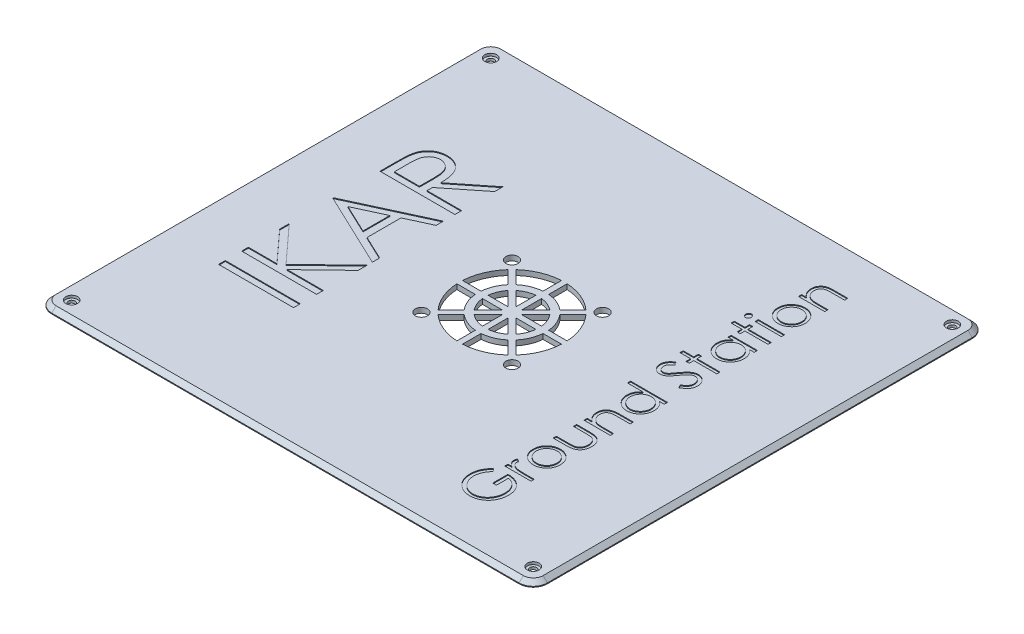
SolidWorks part; units mm, degrees
ref_plane "Płaszczyzna przednia" through (0, 0, 0) normal (0, 0, 1) x (1, 0, 0)
ref_plane "Płaszczyzna górna" through (0, 0, 0) normal (0, 1, 0) x (1, 0, 0)
ref_plane "Płaszczyzna prawa" through (0, 0, 0) normal (1, 0, 0) x (0, 0, -1)
sketch "Szkic1" plane through (0, 0, 0) normal (0, 1, 0) x (1, 0, 0)
  line L1 (87.5, -80) -> (-87.5, -80)
  line L2 (87.5, -80) -> (87.5, 80)
  line L3 (87.5, 80) -> (-87.5, 80)
  line L4 (-87.5, -80) -> (-87.5, 80)
  line L5 (87.5, -80) -> (-87.5, 80) construction
  line L6 (87.5, 80) -> (-87.5, -80) construction
  point P0 (0, 0)
  dimension "D1" = 175
  dimension "D2" = 160
extrude "Dodanie-wyciągnięcie1" add sketch "Szkic1" along normal blind 1.8
fillet "Zaokrąglenie1" radius 5 4 edges at (-87.5, 0.9, -80) (87.5, 0.9, -80) (87.5, 0.9, 80) (-87.5, 0.9, 80)
sketch "Szkic2" plane through (0, 1.8, 0) normal (0, 1, 0) x (1, 0, 0)
  line L0 (82.5, 80) -> (-82.5, 80) construction
  line L1 (-87.5, 75) -> (-87.5, -75) construction
  line L2 (87.5, -75) -> (87.5, 75) construction
  line L3 (-87.5, 0) -> (87.5, 0) construction
  circle A0 centre (-81.5, 74) radius 1.2
  circle A1 centre (81.5, 74) radius 1.2
  circle A2 centre (81.5, -74) radius 1.2
  circle A3 centre (-81.5, -74) radius 1.2
  dimension "D3" = 2.4
  dimension "D4" = 6
  dimension "D6" = 2.4
  dimension "D1" = 6
  dimension "D2" = 6
  dimension "D5" = 6
extrude "Wytnij-wyciągnięcie1" cut sketch "Szkic2" against normal through all
sketch "Szkic3" plane through (0, 1.8, 0) normal (0, 1, 0) x (1, 0, 0)
  line L0 (-16, 0) -> (16, 0) construction
  line L1 (16, 16) -> (16, -16) construction
  line L2 (0, 0) -> (0, 10.869) construction
  line L3 (-1, 0) -> (1, 0) construction
  line L4 (-1, -2.4142) -> (-1, -9.4472)
  line L5 (1, -2.4142) -> (1, -9.4472)
  line L6 (-1, 0) -> (-1, -2.2913) construction
  line L7 (1, 0) -> (1, -2.2913) construction
  line L8 (1, -9.4472) -> (1, -11.9583) construction
  line L9 (1, -11.9583) -> (1, -18.473)
  line L10 (-1, -9.4472) -> (-1, -11.9583) construction
  line L11 (-1, -11.9583) -> (-1, -18.473)
  line L12 (-1, -2.4142) -> (-5.9731, -7.3873)
  line L13 (-2.4142, -1) -> (-7.3873, -5.9731)
  line L14 (-7.7487, -9.1629) -> (-12.3552, -13.7695)
  line L39 (-9.1629, -7.7487) -> (-13.7695, -12.3552)
  line L40 (-2.4142, -1) -> (-9.4472, -1)
  line L41 (-2.4142, 1) -> (-9.4472, 1)
  line L42 (-11.9583, -1) -> (-18.473, -1)
  line L43 (-11.9583, 1) -> (-18.473, 1)
  line L44 (-2.4142, 1) -> (-7.3873, 5.9731)
  line L45 (-1, 2.4142) -> (-5.9731, 7.3873)
  line L46 (-9.1629, 7.7487) -> (-13.7695, 12.3552)
  line L47 (-7.7487, 9.1629) -> (-12.3552, 13.7695)
  line L48 (-1, 2.4142) -> (-1, 9.4472)
  line L49 (1, 2.4142) -> (1, 9.4472)
  line L50 (-1, 11.9583) -> (-1, 18.473)
  line L51 (1, 11.9583) -> (1, 18.473)
  line L52 (1, 2.4142) -> (5.9731, 7.3873)
  line L53 (2.4142, 1) -> (7.3873, 5.9731)
  line L54 (7.7487, 9.1629) -> (12.3552, 13.7695)
  line L55 (9.1629, 7.7487) -> (13.7695, 12.3552)
  line L56 (2.4142, 1) -> (9.4472, 1)
  line L57 (2.4142, -1) -> (9.4472, -1)
  line L58 (11.9583, 1) -> (18.473, 1)
  line L59 (11.9583, -1) -> (18.473, -1)
  line L60 (2.4142, -1) -> (7.3873, -5.9731)
  line L61 (1, -2.4142) -> (5.9731, -7.3873)
  line L62 (9.1629, -7.7487) -> (13.7695, -12.3552)
  line L63 (7.7487, -9.1629) -> (12.3552, -13.7695)
  line L64 (-2.3273, 0.9131) -> (-2.4142, 1) construction
  line L65 (-2.2913, 1) -> (-2.4142, 1) construction
  line L66 (-1, 2.2913) -> (-1, 2.4142) construction
  line L67 (-0.9131, 2.3273) -> (-1, 2.4142) construction
  line L68 (1, 2.2913) -> (1, 2.4142) construction
  line L69 (0.9131, 2.3273) -> (1, 2.4142) construction
  line L70 (2.2913, 1) -> (2.4142, 1) construction
  line L71 (2.3273, 0.9131) -> (2.4142, 1) construction
  line L72 (2.2913, -1) -> (2.4142, -1) construction
  line L73 (2.3273, -0.9131) -> (2.4142, -1) construction
  line L74 (1, -2.2913) -> (1, -2.4142) construction
  line L75 (0.9131, -2.3273) -> (1, -2.4142) construction
  line L76 (-0.9131, -2.3273) -> (-1, -2.4142) construction
  line L77 (-1, -2.2913) -> (-1, -2.4142) construction
  line L78 (-2.3273, -0.9131) -> (-2.4142, -1) construction
  line L79 (-2.2913, -1) -> (-2.4142, -1) construction
  circle A0 centre (16, 16) radius 2.15
  circle A1 centre (16, -16) radius 2.15
  circle A2 centre (-16, -16) radius 2.15
  circle A3 centre (-16, 16) radius 2.15
  circle A13 centre (0, 0) radius 18.5
  arc A17 (2.2913, -1) -> (2.3273, -0.9131) centre (0, 0) ccw construction
  arc A19 (-5.9731, -7.3873) -> (-1, -9.4472) centre (0, 0) ccw
  arc A23 (-7.7487, -9.1629) -> (-1, -11.9583) centre (0, 0) ccw
  arc A27 (-9.1629, -7.7487) -> (-7.7487, -9.1629) centre (0, 0) ccw construction
  arc A30 (-7.3873, -5.9731) -> (-5.9731, -7.3873) centre (0, 0) ccw construction
  arc A31 (7.7487, -9.1629) -> (9.1629, -7.7487) centre (0, 0) ccw construction
  arc A32 (9.1629, -7.7487) -> (11.9583, -1) centre (0, 0) ccw
  arc A34 (5.9731, -7.3873) -> (7.3873, -5.9731) centre (0, 0) ccw construction
  arc A36 (7.3873, -5.9731) -> (9.4472, -1) centre (0, 0) ccw
  arc A38 (1, -2.2913) -> (2.2913, -1) centre (0, 0) ccw construction
  arc A39 (-2.2913, -1) -> (-1, -2.2913) centre (0, 0) ccw construction
  arc A41 (-1, -2.2913) -> (-0.9131, -2.3273) centre (0, 0) ccw construction
  arc A43 (-1, 2.2913) -> (-2.2913, 1) centre (0, 0) ccw construction
  arc A44 (-2.2913, 1) -> (-2.3273, 0.9131) centre (0, 0) ccw construction
  arc A45 (2.2913, 1) -> (1, 2.2913) centre (0, 0) ccw construction
  arc A46 (1, 2.2913) -> (0.9131, 2.3273) centre (0, 0) ccw construction
  arc A47 (9.1629, 7.7487) -> (7.7487, 9.1629) centre (0, 0) ccw construction
  arc A48 (7.7487, 9.1629) -> (1, 11.9583) centre (0, 0) ccw
  arc A49 (7.3873, 5.9731) -> (5.9731, 7.3873) centre (0, 0) ccw construction
  arc A50 (5.9731, 7.3873) -> (1, 9.4472) centre (0, 0) ccw
  arc A51 (1, 11.9583) -> (-1, 11.9583) centre (0, 0) ccw construction
  arc A52 (-1, 11.9583) -> (-7.7487, 9.1629) centre (0, 0) ccw
  arc A53 (0, 9.5) -> (-1, 9.4472) centre (0, 0) ccw construction
  arc A54 (-1, 9.4472) -> (-5.9731, 7.3873) centre (0, 0) ccw
  arc A55 (1, 9.4472) -> (0, 9.5) centre (0, 0) ccw construction
  arc A56 (-7.7487, 9.1629) -> (-9.1629, 7.7487) centre (0, 0) ccw construction
  arc A57 (-9.1629, 7.7487) -> (-11.9583, 1) centre (0, 0) ccw
  arc A58 (-5.9731, 7.3873) -> (-7.3873, 5.9731) centre (0, 0) ccw construction
  arc A59 (-7.3873, 5.9731) -> (-9.4472, 1) centre (0, 0) ccw
  arc A60 (-11.9583, 1) -> (-12, 0) centre (0, 0) ccw construction
  arc A61 (-11.9583, -1) -> (-9.1629, -7.7487) centre (0, 0) ccw
  arc A62 (-9.5, 0) -> (-9.4472, -1) centre (0, 0) ccw construction
  arc A63 (-9.4472, -1) -> (-7.3873, -5.9731) centre (0, 0) ccw
  arc A64 (-9.4472, 1) -> (-9.5, 0) centre (0, 0) ccw construction
  arc A65 (-12, 0) -> (-11.9583, -1) centre (0, 0) ccw construction
  arc A66 (0.9131, 2.3273) -> (0, 2.5) centre (0, 0) ccw construction
  arc A67 (-0.9131, 2.3273) -> (-1, 2.2913) centre (0, 0) ccw construction
  arc A68 (0, 2.5) -> (-0.9131, 2.3273) centre (0, 0) ccw construction
  arc A69 (-2.5, 0) -> (-2.3273, -0.9131) centre (0, 0) ccw construction
  arc A70 (-2.3273, -0.9131) -> (-2.2913, -1) centre (0, 0) ccw construction
  arc A71 (-2.3273, 0.9131) -> (-2.5, 0) centre (0, 0) ccw construction
  arc A72 (2.3273, -0.9131) -> (2.5, 0) centre (0, 0) ccw construction
  arc A73 (2.3273, 0.9131) -> (2.2913, 1) centre (0, 0) ccw construction
  arc A74 (2.5, 0) -> (2.3273, 0.9131) centre (0, 0) ccw construction
  arc A75 (-0.9131, -2.3273) -> (0.9131, -2.3273) centre (0, 0) ccw construction
  arc A76 (0.9131, -2.3273) -> (1, -2.2913) centre (0, 0) ccw construction
  arc A77 (-1, -9.4472) -> (1, -9.4472) centre (0, 0) ccw construction
  arc A78 (1, -9.4472) -> (5.9731, -7.3873) centre (0, 0) ccw
  arc A79 (-1, -11.9583) -> (1, -11.9583) centre (0, 0) ccw construction
  arc A80 (1, -11.9583) -> (7.7487, -9.1629) centre (0, 0) ccw
  arc A81 (9.4472, -1) -> (9.5, 0) centre (0, 0) ccw construction
  arc A82 (9.4472, 1) -> (7.3873, 5.9731) centre (0, 0) ccw
  arc A83 (9.5, 0) -> (9.4472, 1) centre (0, 0) ccw construction
  arc A84 (12, 0) -> (11.9583, 1) centre (0, 0) ccw construction
  arc A85 (11.9583, 1) -> (9.1629, 7.7487) centre (0, 0) ccw
  arc A86 (11.9583, -1) -> (12, 0) centre (0, 0) ccw construction
  circle A87 centre (0, 0) radius 29.0182
  point P20 (0, 0)
  point P86 (0, 0)
  dimension "D3" = 4.3
  dimension "D4" = 4.3
  dimension "D5" = 5
  dimension "D6" = 6.5
  dimension "D9" = 8
  dimension "D1" = 37
  dimension "D7" = 2.5
  dimension "D2" = 32
  dimension "D8" = 2
extrude "Wytnij-wyciągnięcie2" cut sketch "Szkic3" against normal through all contours A2 | A1 | A0 | A3 | A57 L46 A13 L43 | A52 L50 A13 L47 | A48 L54 A13 L51 | A85 L58 A13 L55 | A32 L62 A13 L59 | A80 L9 A13 L63 | A61 L42 A13 L39 | A23 L14 A13 L11 | L12 A19 L4 | L40 A63 L13 | L44 A59 L41 | L48 A54 L45 | L52 A50 L49 | L56 A82 L53 | L60 A36 L57 | L5 A78 L61
sketch "Szkic5" plane through (0, 1.8, 0) normal (0, 1, 0) x (1, 0, 0)
  circle A0 centre (81.5, 74) radius 2.1
  circle A1 centre (81.5, -74) radius 2.1
  circle A2 centre (-81.5, -74) radius 2.1
  circle A3 centre (-81.5, 74) radius 2.1
  dimension "D1" = 4.2
  dimension "D2" = 4.2
  dimension "D3" = 4.2
  dimension "D4" = 4.2
extrude "Wytnij-wyciągnięcie3" cut sketch "Szkic5" against normal blind 0.9 contours A3
chamfer "Sfazowanie2" distance 1.5 angle 45 8 edges at (86.0355, 1.8, -78.5355) (87.5, 1.8, 0) (86.0355, 1.8, 78.5355) (0, 1.8, 80) (-86.0355, 1.8, 78.5355) (-87.5, 1.8, 0) (-86.0355, 1.8, -78.5355) (0, 1.8, -80)
sketch "Szkic6" plane through (0, 1.8, 0) normal (0, -1, 0) x (1, 0, 0)
  line L0 (0, 0) -> (-40, 0) construction
  line L1 (-40, 52.877) -> (-40, -52.877) construction
  line L2 (0, 0) -> (55, 0) construction
  line L3 (55, 71.5448) -> (55, -71.5448) construction
  text T0 "IKAR" font "Century Gothic" height in points 100
  text T1 "Ground Station" font "Century Gothic" height in points 48
  point P6 (-40, 0)
  point P11 (55, 0)
  point P12 (60, 71.5448)
  dimension "D1" = 40
  dimension "D2" = 55
extrude "Wytnij-wyciągnięcie4" cut sketch "Szkic6" along normal blind 0.3
